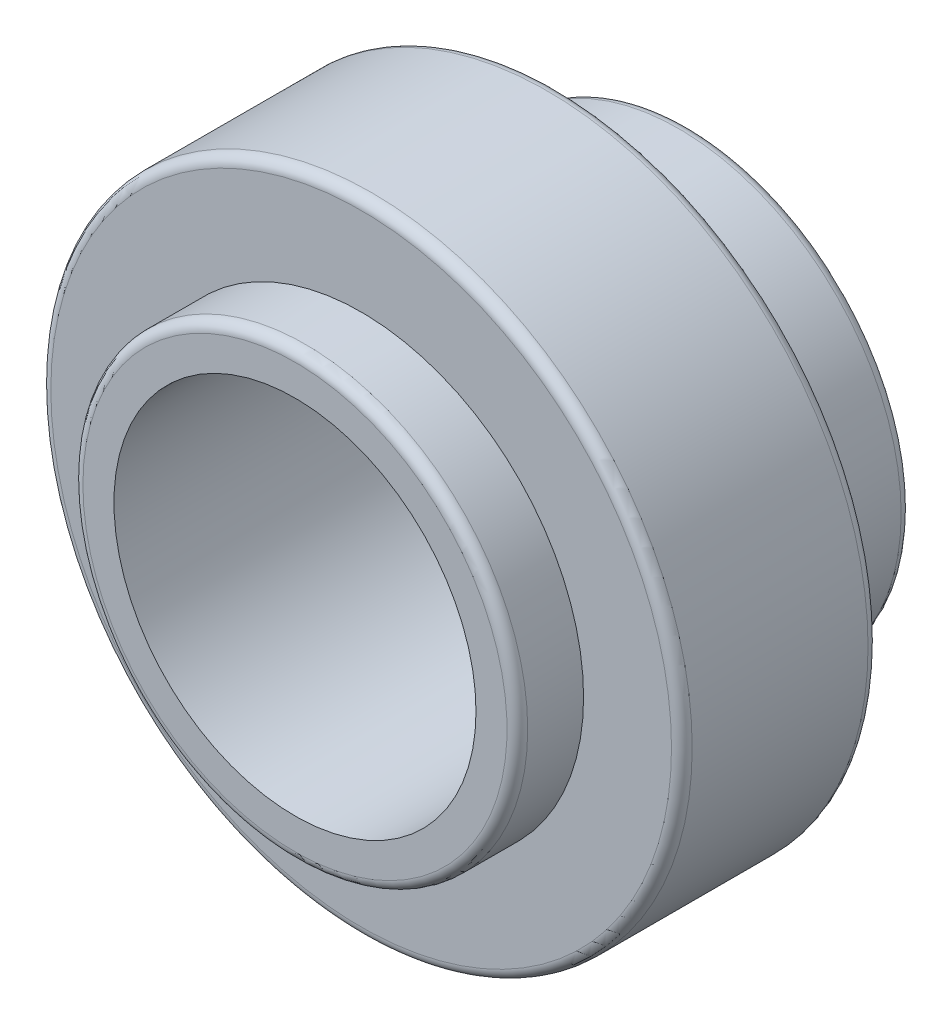
SolidWorks part; units mm, degrees
ref_plane "Płaszczyzna przednia" through (0, 0, 0) normal (0, 0, 1) x (1, 0, 0)
ref_plane "Płaszczyzna górna" through (0, 0, 0) normal (0, 1, 0) x (1, 0, 0)
ref_plane "Płaszczyzna prawa" through (0, 0, 0) normal (1, 0, 0) x (0, 0, -1)
sketch "Szkic2" plane through (0, 0, 0) normal (1, 0, 0) x (0, 0, -1)
  line L0 (-23.4706, 0) -> (29, 0) construction
  line L1 (0, 15.7353) -> (0, -10.0294) construction
  line L2 (-9.5, 21.5) -> (-9.5, 31)
  line L7 (-9.5, 31) -> (9.5, 31)
  line L8 (9.5, 31) -> (9.5, 21.5)
  line L9 (9.5, 21.5) -> (22.2, 21.5)
  line L10 (22.2, 21.5) -> (22.2, 17.5)
  line L11 (22.2, 17.5) -> (-15.9, 17.5)
  line L12 (-15.9, 17.5) -> (-15.9, 21.5)
  line L13 (-15.9, 21.5) -> (-9.5, 21.5)
  point P7 (0, 31)
  dimension "D1" = 19
  dimension "D2" = 62
  dimension "D3" = 35
  dimension "D4" = 15.9
  dimension "D5" = 22.2
  dimension "D6" = 4
revolve "Obrót1" add sketch "Szkic2" angle 360 about L0
fillet "Zaokrąglenie1" radius 1 4 edges at (21.5, 0, 15.9) (31, 0, 9.5) (31, 0, -9.5) (21.5, 0, -22.2)
